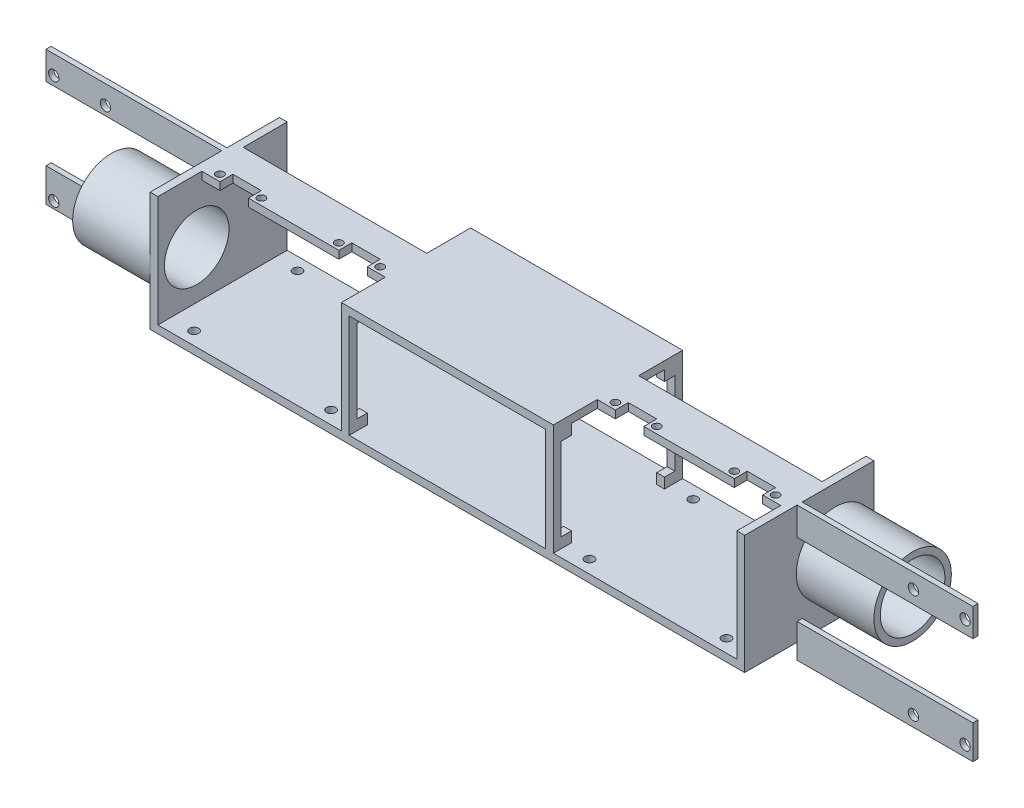
SolidWorks part; units mm, degrees
material "ABS PC"
ref_plane "Front Plane" through (0, 0, 0) normal (0, 0, 1) x (1, 0, 0)
ref_plane "Top Plane" through (0, 0, 0) normal (0, 1, 0) x (1, 0, 0)
ref_plane "Right Plane" through (0, 0, 0) normal (1, 0, 0) x (0, 0, -1)
sketch "Sketch1" plane through (0, 0, 0) normal (0, 0, 1) x (1, 0, 0)
  line L1 (-41, -23) -> (41, -23)
  line L2 (-41, -23) -> (-41, 23)
  line L3 (-41, 23) -> (41, 23)
  line L4 (41, -23) -> (41, 23)
  line L5 (-41, -23) -> (41, 23) construction
  line L6 (-41, 23) -> (41, -23) construction
  point P0 (0, 0)
  dimension "D1" = 82
  dimension "D2" = 46
extrude "Boss-Extrude1" add sketch "Sketch1" along normal mid plane 50
sketch "Sketch2" plane through (0, 0, 25) normal (0, 0, 1) x (1, 0, 0)
  line L0 (41, 23) -> (-41, 23) construction
  line L1 (-38, 20) -> (38, 20)
  line L2 (-38, 20) -> (-38, -20)
  line L3 (-38, -20) -> (38, -20)
  line L4 (38, 20) -> (38, -20)
  line L5 (-38, 20) -> (38, -20) construction
  line L6 (-38, -20) -> (38, 20) construction
  line L7 (-41, 23) -> (-41, -23) construction
  point P0 (0, 0)
  dimension "D1" = 3
  dimension "D2" = 3
extrude "Cut-Extrude1" cut sketch "Sketch2" against normal up to next
sketch "Sketch3" plane through (-41, 0, 0) normal (-1, 0, 0) x (0, 0, 1)
  line L0 (-18, 16) -> (-18, 20)
  line L1 (-18, 20) -> (18, 20)
  line L2 (18, 20) -> (18, 16)
  line L3 (18, 16) -> (22, 16)
  line L4 (22, 16) -> (22, -16)
  line L5 (22, -16) -> (18, -16)
  line L6 (18, -16) -> (18, -20)
  line L7 (18, -20) -> (-18, -20)
  line L8 (-18, -20) -> (-18, -16)
  line L9 (-18, -16) -> (-22, -16)
  line L10 (-22, -16) -> (-22, 16)
  line L11 (-22, 16) -> (-18, 16)
  line L12 (25, 23) -> (-25, 23) construction
  line L13 (-25, 23) -> (-25, -23) construction
  line L14 (25, 23) -> (25, -23) construction
  line L15 (25, -23) -> (-25, -23) construction
  dimension "D1" = 3
  dimension "D2" = 3
  dimension "D3" = 3
  dimension "D4" = 3
  dimension "D5" = 7
  dimension "D6" = 7
  dimension "D7" = 7
  dimension "D8" = 7
  dimension "D9" = 7
  dimension "D10" = 7
  dimension "D11" = 7
  dimension "D12" = 7
extrude "Cut-Extrude2" cut sketch "Sketch3" against normal through all both and the other way through all
sketch "Sketch4" plane through (41, 0, 0) normal (1, 0, 0) x (0, 0, -1)
  line L0 (25, -23) -> (25, 23) construction
  line L1 (-25, -23) -> (25, -23)
  line L2 (-25, -23) -> (-25, -20)
  line L3 (-25, -20) -> (25, -20)
  line L4 (25, -23) -> (25, -20)
  dimension "D1" = 3
extrude "Boss-Extrude2" add sketch "Sketch4" along normal blind 71
sketch "Sketch5" plane through (0, -20, 0) normal (0, 1, 0) x (1, 0, 0)
  line L2 (112, -25) -> (41, -25) construction
  line L3 (41, -18) -> (41, -25) construction
  line L4 (41, 25) -> (41, 18) construction
  circle A0 centre (103.1, 20.1) radius 1.75
  circle A1 centre (103, -20) radius 1.75
  circle A2 centre (50, 20.1) radius 1.75
  circle A3 centre (50, -20) radius 1.75
  dimension "D1" = 3.5
  dimension "D2" = 3.5
  dimension "D3" = 3.5
  dimension "D4" = 3.5
  dimension "D5" = 53
  dimension "D6" = 53.1
  dimension "D7" = 9
  dimension "D8" = 9
  dimension "D9" = 40.1
  dimension "D10" = 40.1
  dimension "D11" = 5
  dimension "D12" = 5
extrude "Cut-Extrude3" cut sketch "Sketch5" against normal up to next
sketch "Sketch6" plane through (41, 0, 0) normal (1, 0, 0) x (0, 0, -1)
  line L1 (-25, 23) -> (-18, 23)
  line L2 (-25, 23) -> (-25, 16)
  line L3 (-25, 16) -> (-18, 16)
  line L4 (-18, 23) -> (-18, 16)
  line L5 (25, 23) -> (18, 23)
  line L6 (25, 23) -> (25, 16)
  line L7 (25, 16) -> (18, 16)
  line L8 (18, 23) -> (18, 16)
  point P10 (-18, 19.5)
  dimension "D1" = 7
  dimension "D2" = 7
  dimension "D3" = 7
  dimension "D4" = 7
sketch "Sketch7" plane through (41, 0, 0) normal (1, 0, 0) x (0, 0, -1)
  line L0 (-25, 23) -> (25, 23) construction
  line L1 (-8, 23) -> (8, 23)
  line L2 (-8, 23) -> (-8, 20)
  line L3 (-8, 20) -> (8, 20)
  line L4 (8, 23) -> (8, 20)
  line L5 (-18, 20) -> (18, 20) construction
  line L6 (-25, 23) -> (-25, 16) construction
  dimension "D1" = 16
  dimension "D2" = 17
extrude "Boss-Extrude4" add sketch "Sketch7" along normal blind 71
sketch "Sketch8" plane through (112, 0, 0) normal (1, 0, 0) x (0, 0, -1)
  line L1 (-25, -23) -> (25, -23)
  line L2 (-25, -23) -> (-25, 23)
  line L3 (-25, 23) -> (25, 23)
  line L4 (25, -23) -> (25, 23)
  dimension "D1" = 46
  dimension "D2" = 50
extrude "Boss-Extrude5" add sketch "Sketch8" along normal blind 3
sketch "Sketch9" plane through (0, 23, 0) normal (0, 1, 0) x (1, 0, 0)
  line L0 (105, -8) -> (105, -3)
  line L1 (112, -8) -> (41, -8) construction
  line L2 (105, -3) -> (94, -3)
  line L3 (94, -3) -> (94, -8)
  line L4 (112, -8) -> (112, -25) construction
  dimension "D1" = 7
  dimension "D2" = 18
  dimension "D3" = 5
extrude "Cut-Extrude4" cut sketch "Sketch9" against normal blind 3 and the other way through all
sketch "Sketch10" plane through (0, 23, 0) normal (0, 1, 0) x (1, 0, 0)
  line L0 (48, -8) -> (48, -3)
  line L1 (94, -8) -> (41, -8) construction
  line L2 (48, -3) -> (59, -3)
  line L3 (59, -3) -> (59, -8)
  line L4 (59, -8) -> (48, -8)
  line L5 (41, -25) -> (41, -8) construction
  dimension "D1" = 5
  dimension "D2" = 11
  dimension "D3" = 7
extrude "Cut-Extrude5" cut sketch "Sketch10" against normal up to next
sketch "Sketch11" plane through (0, 23, 0) normal (0, 1, 0) x (1, 0, 0)
  line L0 (112, -8) -> (105, -8) construction
  line L1 (105, -3) -> (105, -8) construction
  line L2 (94, -8) -> (94, -3) construction
  line L3 (94, -8) -> (59, -8) construction
  line L4 (59, -8) -> (59, -3) construction
  line L5 (48, -8) -> (41, -8) construction
  line L6 (48, -3) -> (48, -8) construction
  circle A0 centre (45.5, -5.5) radius 1.5
  circle A1 centre (61.5, -5.5) radius 1.5
  circle A2 centre (91.5, -5.5) radius 1.5
  circle A3 centre (107.5, -5.5) radius 1.5
  dimension "D1" = 3
  dimension "D2" = 3
  dimension "D3" = 3
  dimension "D4" = 3
  dimension "D5" = 2.5
  dimension "D6" = 2.5
  dimension "D7" = 2.5
  dimension "D8" = 2.5
  dimension "D9" = 2.5
  dimension "D10" = 2.5
  dimension "D11" = 2.5
  dimension "D12" = 2.5
extrude "Cut-Extrude6" cut sketch "Sketch11" against normal up to next
sketch "Sketch12" plane through (115, 0, 0) normal (1, 0, 0) x (0, 0, -1)
  line L0 (25, -23) -> (25, 23) construction
  circle A0 centre (10, 0) radius 15
  dimension "D1" = 30
  dimension "D2" = 15
extrude "Boss-Extrude6" add sketch "Sketch12" along normal blind 30
sketch "Sketch13" plane through (145, 0, 0) normal (1, 0, 0) x (0, 0, -1)
  line L0 (25, -23) -> (25, 0) construction
  circle A0 centre (10, 0) radius 12.5
  dimension "D1" = 25
  dimension "D2" = 15
extrude "Cut-Extrude7" cut sketch "Sketch13" against normal through all
sketch "Sketch14" plane through (115, 0, 0) normal (1, 0, 0) x (0, 0, -1)
  line L0 (25, 23) -> (-25, 23) construction
  line L1 (-4.7, 23) -> (-2.7, 23)
  line L2 (-4.7, 23) -> (-4.7, 12.2)
  line L3 (-4.7, 12.2) -> (-2.7, 12.2)
  line L4 (-2.7, 23) -> (-2.7, 12.2)
  line L10 (-25, 23) -> (-25, 16) construction
  line L11 (-25, 23) -> (-25, -23) construction
  line L12 (-4.7, -16) -> (-2.7, -16)
  line L13 (-4.7, -16) -> (-4.7, -29)
  line L14 (-4.7, -29) -> (-2.7, -29)
  line L15 (-2.7, -16) -> (-2.7, -29)
  line L16 (-25, -23) -> (25, -23) construction
  dimension "D1" = 10.8
  dimension "D2" = 22.3
  dimension "D3" = 2
  dimension "D4" = 13
  dimension "D5" = 22.3
  dimension "D6" = 2
  dimension "D7" = 7
extrude "Boss-Extrude7" add sketch "Sketch14" along normal blind 68
sketch "Sketch15" plane through (0, 0, 2.7) normal (0, 0, -1) x (-1, 0, 0)
  line L0 (-183, 12.2) -> (-115, 12.2) construction
  line L1 (-183, 23) -> (-183, 12.2) construction
  line L2 (-115, 23) -> (-115, 12.2) construction
  circle A0 centre (-180, -24.8) radius 2
  circle A1 centre (-160, -24.8) radius 2
  circle A2 centre (-160, 17.2) radius 2
  circle A3 centre (-180, 17.2) radius 2
  dimension "D1" = 4
  dimension "D2" = 4
  dimension "D3" = 4
  dimension "D4" = 4
extrude "Cut-Extrude8" cut sketch "Sketch15" against normal up to next
mirror "Mirror1" about plane through (0, 0, 0) normal (1, 0, 0) of "Cut-Extrude6", "Cut-Extrude5", "Boss-Extrude5", "Boss-Extrude2", "Cut-Extrude3", "Boss-Extrude4", "Cut-Extrude4"
sketch "Sketch16" plane through (-115, 0, 0) normal (-1, 0, 0) x (0, 0, 1)
  line L0 (25, 23) -> (25, -23) construction
  circle A0 centre (10, -1.5051) radius 15
  dimension "D1" = 30
  dimension "D2" = 15
extrude "Boss-Extrude8" add sketch "Sketch16" along normal blind 30
sketch "Sketch17" plane through (-145, 0, 0) normal (-1, 0, 0) x (0, 0, 1)
  circle A0 centre (10, -1.5051) radius 12.5
  dimension "D1" = 25
extrude "Cut-Extrude9" cut sketch "Sketch17" against normal up to next
sketch "Sketch18" plane through (-115, 0, 0) normal (-1, 0, 0) x (0, 0, 1)
  line L1 (-4.7, 12.2) -> (-2.7, 12.2)
  line L2 (-4.7, 12.2) -> (-4.7, 23)
  line L3 (-4.7, 23) -> (-2.7, 23)
  line L4 (-2.7, 12.2) -> (-2.7, 23)
  line L5 (-25, -23) -> (-25, 23) construction
  line L6 (-25, 23) -> (25, 23) construction
  dimension "D1" = 10.8
  dimension "D2" = 22.3
  dimension "D3" = 2
  dimension "D4" = 0
extrude "Boss-Extrude9" add sketch "Sketch18" along normal blind 68
sketch "Sketch19" plane through (-115, 0, 0) normal (-1, 0, 0) x (0, 0, 1)
  line L0 (25, -23) -> (-25, -23) construction
  line L1 (-4.7, -29) -> (-2.7, -29)
  line L2 (-4.7, -29) -> (-4.7, -16)
  line L3 (-4.7, -16) -> (-2.7, -16)
  line L4 (-2.7, -29) -> (-2.7, -16)
  line L5 (-25, -23) -> (-25, 23) construction
  dimension "D1" = 13
  dimension "D2" = 7
  dimension "D3" = 22.3
  dimension "D4" = 2
extrude "Boss-Extrude10" add sketch "Sketch19" along normal blind 68
sketch "Sketch20" plane through (0, 0, -2.7) normal (0, 0, 1) x (1, 0, 0)
  line L6 (-183, 12.2) -> (-115, 12.2) construction
  circle A0 centre (-160, 15.6949) radius 2
  circle A1 centre (-180, 15.6949) radius 2
  circle A2 centre (-160, -26.3051) radius 2
  circle A3 centre (-180, -26.3051) radius 2
extrude "Cut-Extrude10" cut sketch "Sketch20" against normal up to next
